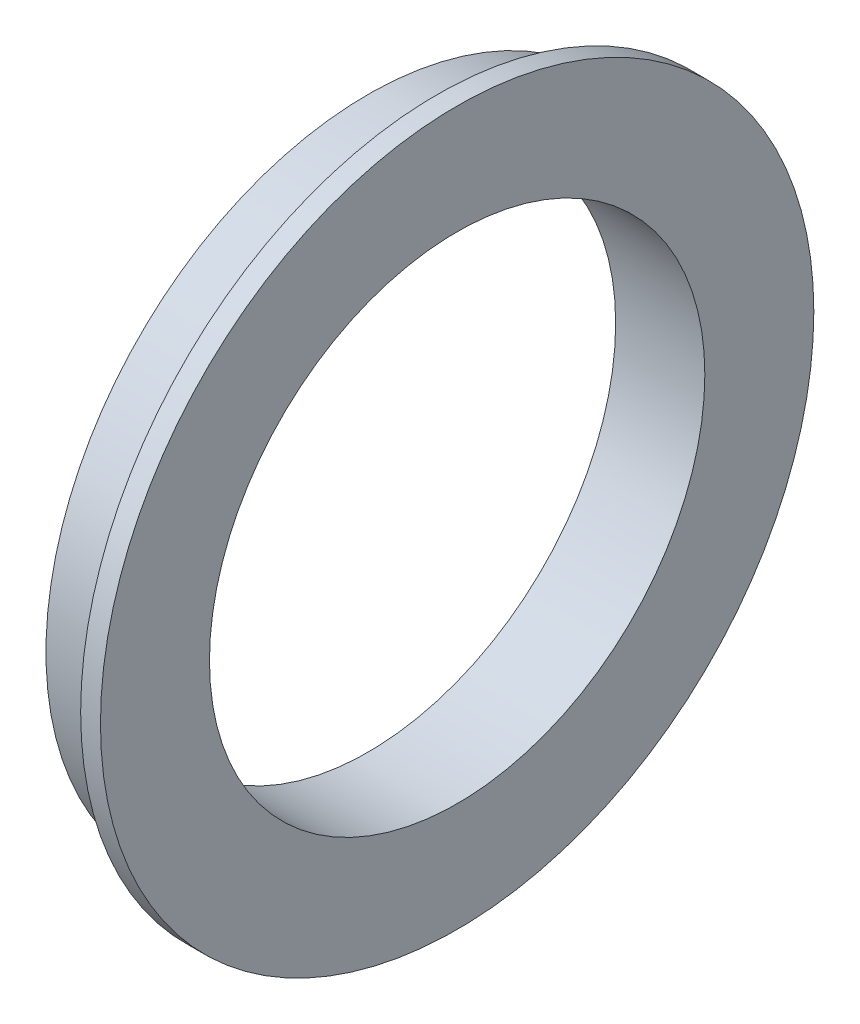
SolidWorks part; units mm, degrees
ref_plane "Front Plane" through (0, 0, 0) normal (0, 0, 1) x (1, 0, 0)
ref_plane "Top Plane" through (0, 0, 0) normal (0, 1, 0) x (1, 0, 0)
ref_plane "Right Plane" through (0, 0, 0) normal (1, 0, 0) x (0, 0, -1)
sketch "Sketch1" plane through (0, 0, 0) normal (1, 0, 0) x (0, 0, -1)
  circle A0 centre (0, 0) radius 25
  circle A1 centre (0, 0) radius 32.5
  dimension "D1" = 50
  dimension "D2" = 65
extrude "Boss-Extrude1" add sketch "Sketch1" along normal blind 7
sketch "Sketch2" plane through (7, 0, 0) normal (1, 0, 0) x (0, 0, -1)
  circle A0 centre (0, 0) radius 36
  circle A1 centre (0, 0) radius 25 construction
  circle A2 centre (0, 0) radius 25
  dimension "D1" = 72
extrude "Boss-Extrude2" add sketch "Sketch2" along normal blind 2
